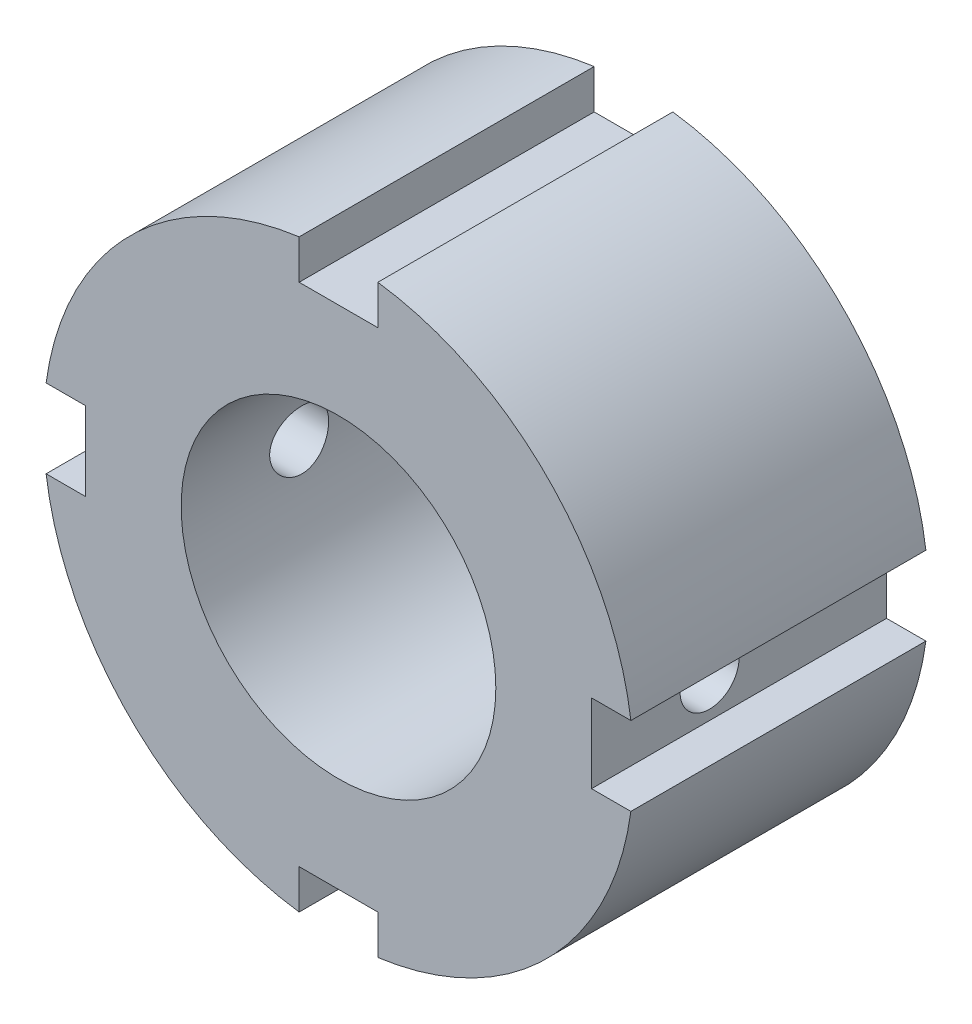
SolidWorks part; units mm, degrees
ref_plane "Plano frontal" through (0, 0, 0) normal (0, 0, 1) x (1, 0, 0)
ref_plane "Plano superior" through (0, 0, 0) normal (0, 1, 0) x (1, 0, 0)
ref_plane "Plano direito" through (0, 0, 0) normal (1, 0, 0) x (0, 0, -1)
sketch "Esboço1" plane through (0, 0, 0) normal (0, 0, 1) x (1, 0, 0)
  line L0 (-32.2012, 0) -> (32.2012, 0) construction
  line L1 (0, 25.3337) -> (0, -25.3337) construction
  line L2 (-2, 12.8661) -> (2, 12.8661)
  line L3 (2, 12.8661) -> (2, 14.8661)
  line L4 (-2, 12.8661) -> (-2, 14.8661)
  line L5 (12.8661, 2) -> (12.8661, -2)
  line L6 (12.8661, -2) -> (14.8661, -2)
  line L7 (12.8661, 2) -> (14.8661, 2)
  line L8 (-2, -12.8661) -> (2, -12.8661)
  line L9 (2, -12.8661) -> (2, -14.8661)
  line L10 (-2, -12.8661) -> (-2, -14.8661)
  line L11 (-12.8661, -2) -> (-14.8661, -2)
  line L12 (-12.8661, 2) -> (-12.8661, -2)
  line L13 (-12.8661, 2) -> (-14.8661, 2)
  circle A0 centre (0, 0) radius 8
  circle A1 centre (0, 0) radius 15
  point P7 (0, 0)
  point P10 (0, 0)
  point P13 (0, 12.8661)
  point P18 (12.8661, 0)
  dimension "D1" = 30
  dimension "D2" = 16
  dimension "D3" = 4
  dimension "D4" = 2
extrude "Ressalto-extrusão1" add sketch "Esboço1" along normal blind 15 contours L7 A1 L3 L2 L4 L13 L12 L11 L10 L8 L9 L6 L5 A0
sketch "Esboço2" plane through (0, 0, 0) normal (1, 0, 0) x (0, 0, -1)
  line L0 (-15, 2) -> (-15, -2) construction
  circle A0 centre (-9, 0) radius 1.5
  dimension "D1" = 3
  dimension "D2" = 6
extrude "Corte-extrusão1" cut sketch "Esboço2" against normal through all both and the other way through all
